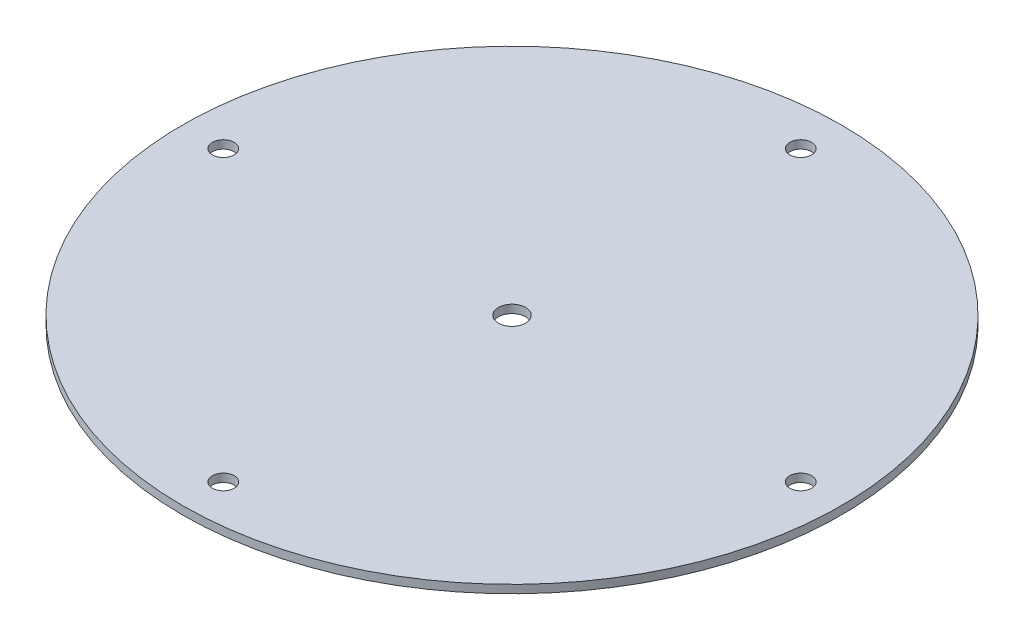
SolidWorks part; units mm, degrees
ref_plane "Front Plane" through (0, 0, 0) normal (0, 0, 1) x (1, 0, 0)
ref_plane "Top Plane" through (0, 0, 0) normal (0, 1, 0) x (1, 0, 0)
ref_plane "Right Plane" through (0, 0, 0) normal (1, 0, 0) x (0, 0, -1)
sketch "Sketch1" plane through (0, 0, 0) normal (0, 1, 0) x (1, 0, 0)
  circle A0 centre (0, 0) radius 60.5
  circle A1 centre (0, 0) radius 2.5
extrude "Boss-Extrude1" add sketch "Sketch1" along normal blind 1.5
sketch "Sketch2" plane through (0, 1.5, 0) normal (0, 1, 0) x (1, 0, 0)
  circle A0 centre (0, 53) radius 2
  circle A1 centre (53, 0) radius 2
  circle A2 centre (0, -53) radius 2
  circle A3 centre (-53, 0) radius 2
  point P12 (0, 0)
  dimension "D1" = 4
extrude "Cut-Extrude1" cut sketch "Sketch2" against normal through all
